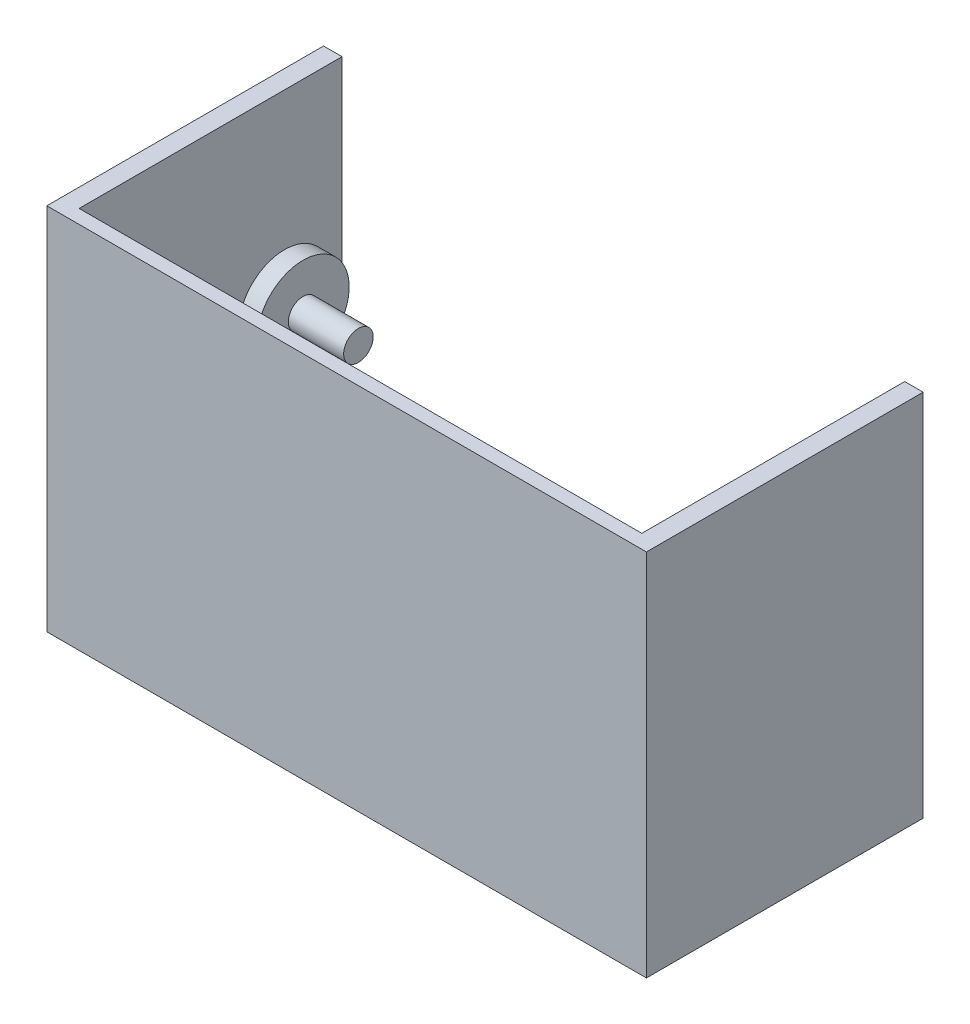
SolidWorks part; units mm, degrees
ref_plane "Plano frontal" through (0, 0, 0) normal (0, 0, 1) x (1, 0, 0)
ref_plane "Plano superior" through (0, 0, 0) normal (0, 1, 0) x (1, 0, 0)
ref_plane "Plano direito" through (0, 0, 0) normal (1, 0, 0) x (0, 0, -1)
sketch "Esboço1" plane through (0, 0, 0) normal (0, 0, 1) x (1, 0, 0)
  line L1 (32.5, 20) -> (-32.5, 20)
  line L2 (32.5, 20) -> (32.5, -20)
  line L3 (32.5, -20) -> (-32.5, -20)
  line L4 (-32.5, 20) -> (-32.5, -20)
  line L5 (32.5, 20) -> (-32.5, -20) construction
  line L6 (32.5, -20) -> (-32.5, 20) construction
  point P0 (0, 0)
  dimension "D1" = 65
  dimension "D2" = 40
extrude "Ressalto-extrusão1" add sketch "Esboço1" along normal blind 30
sketch "Esboço2" plane through (0, 0, 0) normal (0, 0, -1) x (-1, 0, 0)
  line L0 (-32.5, 20) -> (32.5, 20) construction
  line L1 (30.5, 18.5) -> (-30.5, 18.5)
  line L2 (30.5, 18.5) -> (30.5, -18.5)
  line L3 (30.5, -18.5) -> (-30.5, -18.5)
  line L4 (-30.5, 18.5) -> (-30.5, -18.5)
  line L5 (30.5, 18.5) -> (-30.5, -18.5) construction
  line L6 (30.5, -18.5) -> (-30.5, 18.5) construction
  line L8 (-32.5, -20) -> (-32.5, 20) construction
  point P0 (0, 0)
  dimension "D1" = 1.5
  dimension "D2" = 2
extrude "Corte-extrusão1" cut sketch "Esboço2" against normal blind 20
sketch "Esboço3" plane through (0, 20, 0) normal (0, 1, 0) x (1, 0, 0)
  line L0 (32.5, 0) -> (-32.5, 0) construction
  line L1 (30.5, -1.5) -> (-30.5, -1.5)
  line L2 (30.5, -1.5) -> (30.5, -28.5)
  line L3 (30.5, -28.5) -> (-30.5, -28.5)
  line L4 (-30.5, -1.5) -> (-30.5, -28.5)
  line L5 (30.5, -1.5) -> (-30.5, -28.5) construction
  line L6 (30.5, -28.5) -> (-30.5, -1.5) construction
  line L7 (32.5, -30) -> (-32.5, -30) construction
  line L8 (-32.5, -30) -> (-32.5, 0) construction
  line L9 (32.5, -30) -> (32.5, 0) construction
  point P0 (0, -15)
  dimension "D1" = 1.5
  dimension "D2" = 1.5
  dimension "D3" = 2
  dimension "D4" = 2
extrude "Corte-extrusão2" cut sketch "Esboço3" against normal blind 49
sketch "Esboço5" plane through (0, 20, 0) normal (0, 1, 0) x (1, 0, 0)
  line L0 (32.5, 0) -> (-32.5, 0) construction
  line L1 (-30.5, -1.5) -> (30.5, -1.5)
  line L2 (-30.5, -1.5) -> (-30.5, 0)
  line L3 (-30.5, 0) -> (30.5, 0)
  line L4 (30.5, -1.5) -> (30.5, 0)
extrude "Corte-extrusão3" cut sketch "Esboço5" against normal blind 49
sketch "Esboço7" plane through (-32.5, 0, 0) normal (-1, 0, 0) x (0, 0, 1)
  circle A0 centre (6.2249, 0) radius 5
  dimension "D1" = 10
extrude "Ressalto-extrusão2" add sketch "Esboço7" against normal blind 4
sketch "Esboço8" plane through (-28.5, 0, 0) normal (1, 0, 0) x (0, 0, -1)
  circle A0 centre (-6.2249, 0) radius 1.6
  dimension "D1" = 3.2
extrude "Ressalto-extrusão3" add sketch "Esboço8" along normal blind 6
sketch "Esboço10" plane through (32.5, 0, 0) normal (1, 0, 0) x (0, 0, -1)
  circle A0 centre (-6.2249, 0) radius 3.5
  dimension "D1" = 7
extrude "Ressalto-extrusão4" add sketch "Esboço10" against normal blind 6
sketch "Esboço12" plane through (26.5, 0, 0) normal (-1, 0, 0) x (0, 0, 1)
  circle A0 centre (6.2249, 0) radius 2.75
  dimension "D1" = 5.5
extrude "Corte-extrusão4" cut sketch "Esboço12" against normal blind 4
